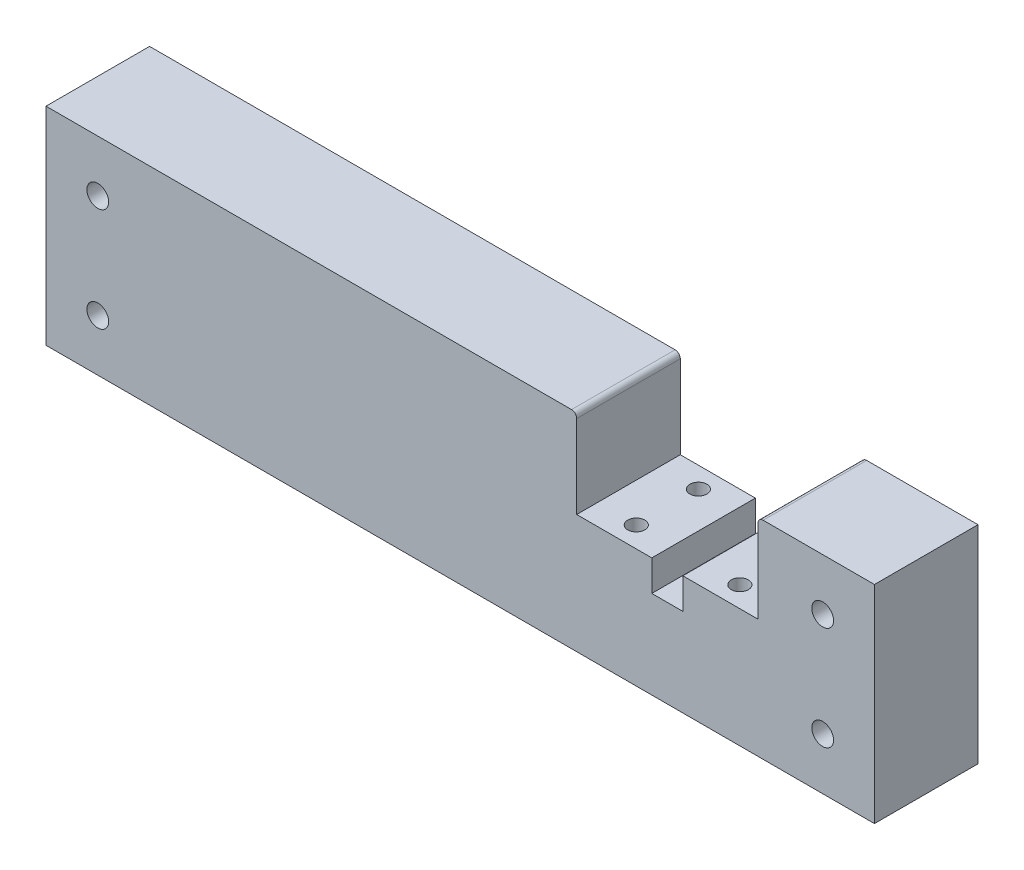
SolidWorks part; units mm, degrees
material "6061-T6 (SS)"
ref_plane "Front Plane" through (0, 0, 0) normal (0, 0, 1) x (1, 0, 0)
ref_plane "Top Plane" through (0, 0, 0) normal (0, 1, 0) x (1, 0, 0)
ref_plane "Right Plane" through (0, 0, 0) normal (1, 0, 0) x (0, 0, -1)
sketch "Sketch1" plane through (0, 0, 0) normal (0, 0, 1) x (1, 0, 0)
  line L0 (-70, 30) -> (-70, 10) construction
  line L1 (-80, 40) -> (80, 40)
  line L2 (-80, 40) -> (-80, 0)
  line L3 (-80, 0) -> (80, 0)
  line L4 (80, 40) -> (80, 0)
  line L9 (37, 23) -> (43, 23) construction
  line L10 (37, 23) -> (37, 17) construction
  line L11 (37, 17) -> (43, 17) construction
  line L12 (43, 23) -> (43, 17) construction
  line L13 (0, 0) -> (0, 40) construction
  line L14 (37, 20) -> (43, 20) construction
  line L15 (40, 17) -> (40, 23) construction
  line L16 (22.5, 40) -> (22.5, 22.95)
  line L17 (22.5, 40) -> (57.5, 40) construction
  line L18 (22.5, 40) -> (22.5, 23) construction
  line L19 (22.5, 23) -> (57.5, 23) construction
  line L20 (57.5, 40) -> (57.5, 23) construction
  line L21 (22.5, 22.95) -> (37, 22.95)
  line L22 (37, 22.95) -> (37, 17)
  line L23 (37, 17) -> (43, 17)
  line L24 (43, 17) -> (43, 22.95)
  line L25 (43, 22.95) -> (57.5, 22.95)
  line L26 (57.5, 22.95) -> (57.5, 40)
  circle A0 centre (-70, 30) radius 2.5 construction
  circle A1 centre (-70, 10) radius 2.5 construction
  circle A2 centre (70, 10) radius 2.5 construction
  circle A3 centre (70, 30) radius 2.5 construction
  point P10 (0, 0)
  point P15 (80, 20)
  point P31 (40, 23)
  dimension "D8" = 5
  dimension "D10" = 10
  dimension "D2" = 160
  dimension "D3" = 40
  dimension "D4" = 40
  dimension "D5" = 35
  dimension "D6" = 6
  dimension "D7" = 20
  dimension "D9" = 10
  dimension "D11" = 0.05
extrude "Boss-Extrude1" add sketch "Sketch1" against normal blind 20
sketch "Sketch4" plane through (0, 0, 0) normal (0, -1, 0) x (1, 0, 0)
  line L0 (-60, -10) -> (60, -10) construction
  line L2 (-80, 0) -> (80, 0)
  line L3 (-80, 0) -> (-80, -20)
  line L4 (-80, -20) -> (80, -20)
  line L5 (80, 0) -> (80, -20)
  circle A0 centre (0, -10) radius 2.5 construction
  circle A1 centre (60, -10) radius 2.5 construction
  circle A2 centre (-60, -10) radius 2.5 construction
  point P6 (0, -10)
  point P14 (80, -10)
  dimension "D1" = 5
  dimension "D2" = 120
sketch "Sketch8" plane through (0, 22.95, 0) normal (0, 1, 0) x (1, 0, 0)
  line L8 (37, 0) -> (22.5, 0) construction
  line L9 (22.5, 0) -> (22.5, 20) construction
  line L10 (22.5, 20) -> (37, 20) construction
  line L11 (37, 20) -> (37, 0) construction
  line L12 (57.5, 0) -> (43, 0) construction
  line L13 (43, 0) -> (43, 20) construction
  line L14 (43, 20) -> (57.5, 20) construction
  line L15 (57.5, 20) -> (57.5, 0) construction
  line L16 (30, 4) -> (50, 4) construction
  line L17 (37, 20) -> (43, 20)
  line L18 (37, 20) -> (37, 0) construction
  line L19 (37, 20) -> (37, 0) construction
  line L20 (30, 4) -> (30, 16) construction
  line L21 (30, 16) -> (50, 16) construction
  line L22 (50, 16) -> (50, 4) construction
  circle A0 centre (50, 4) radius 2 construction
  circle A1 centre (30, 4) radius 2 construction
  circle A2 centre (30, 16) radius 2 construction
  circle A3 centre (50, 16) radius 2 construction
  point P4 (40, 4)
  point P5 (40, 20)
  point P17 (50, 10)
  point P18 (43, 10)
  dimension "D1" = 4
  dimension "D2" = 20
  dimension "D3" = 12
hole_wizard "Tap Drill for M4x0.7 Tap1" positions "3DSketch3" profile "Sketch9" hole size "M4x0.7" standard "ANSI Metric"
sketch3d "3DSketch3"
  point P10 (30, 22.95, -4)
  point P12 (50, 22.95, -4)
  point P19 (30, 22.95, -16)
  point P21 (50, 22.95, -16)
sketch "Sketch9" plane through (30, 22.95, -4) normal (1, 0, 0) x (0, 0, 1)
  line L0 (0, 0) -> (0, 5.9914)
  line L1 (0, 5.9914) -> (1.65, 5)
  line L2 (1.65, 5) -> (1.65, 0)
  line L5 (1.65, 0) -> (0, 0)
  line L10 (0, 5.9914) -> (-1.65, 5) construction
  line L11 (0, -6.35) -> (0, 107.95) construction
  dimension "Hole Dia." = 3.3
  dimension "Hole Depth" = 5
  dimension "Drill Angle" = 118
hole_wizard "Tap Drill for M5x0.8 Tap3" positions "3DSketch4" profile "Sketch10" hole size "M5x0.8" standard "ANSI Metric" end condition up to next
sketch3d "3DSketch4"
  point P0 (-70, 30, 0)
  point P2 (-70, 10, 0)
  point P4 (70, 10, 0)
  point P6 (70, 30, 0)
sketch "Sketch10" plane through (-70, 30, 0) normal (1, 0, 0) x (0, -1, 0)
  line L0 (0, 0) -> (0, 20)
  line L1 (0, 20) -> (2.1, 20)
  line L2 (2.1, 20) -> (2.1, 0)
  line L5 (2.1, 0) -> (0, 0)
  line L11 (0, -6.35) -> (0, 107.95) construction
  dimension "Thru Hole Dia." = 4.2
  dimension "Thru Hole Depth" = 20
hole_wizard "Tap Drill for M5x0.8 Tap2" positions "3DSketch2" profile "Sketch5" hole size "M5x0.8" standard "ANSI Metric"
sketch3d "3DSketch2"
  point P0 (-60, 0, -10)
  point P2 (0, 0, -10)
  point P4 (60, 0, -10)
sketch "Sketch5" plane through (-60, 0, -10) normal (1, 0, 0) x (0, 0, -1)
  line L0 (0, 0) -> (0, 8.2618)
  line L1 (0, 8.2618) -> (2.1, 7)
  line L2 (2.1, 7) -> (2.1, 0)
  line L5 (2.1, 0) -> (0, 0)
  line L10 (0, 8.2618) -> (-2.1, 7) construction
  line L11 (0, -6.35) -> (0, 107.95) construction
  dimension "Hole Dia." = 4.2
  dimension "Hole Depth" = 7
  dimension "Drill Angle" = 118
fillet "Fillet1" radius 1 2 edges at (57.5, 40, -10) (22.5, 40, -10)
ref_plane "Plane1" through (0, 0, -10) normal (0, 0, -1) x (-1, 0, 0)
